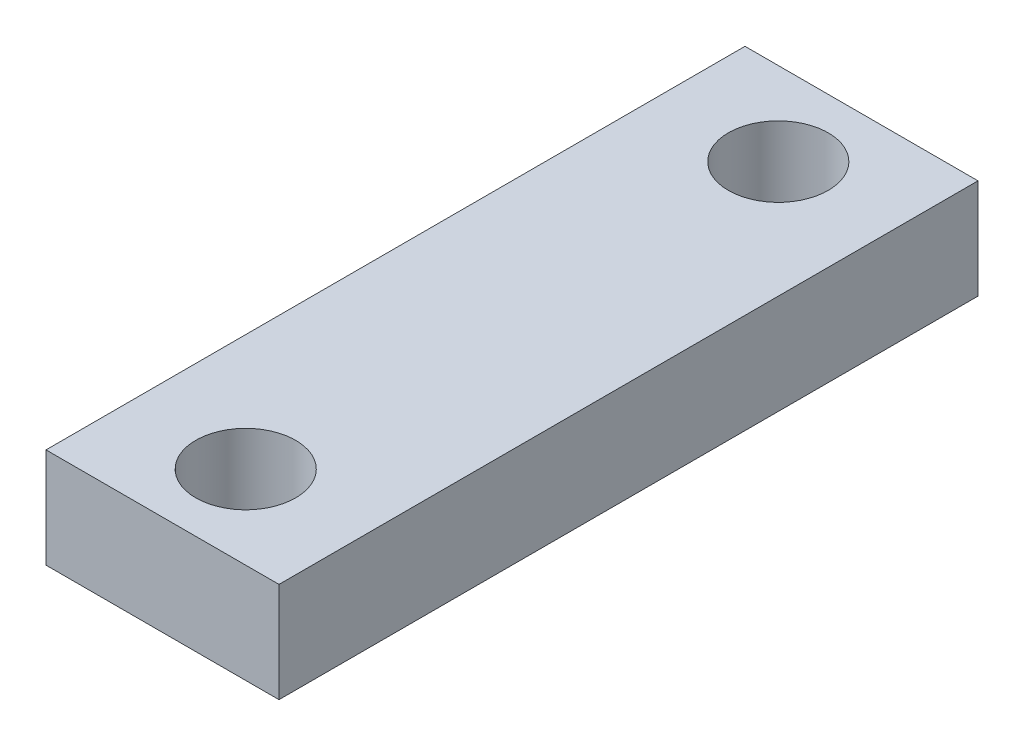
SolidWorks part; units mm, degrees
material "Alloy Steel"
ref_plane "Front Plane" through (0, 0, 0) normal (0, 0, 1) x (1, 0, 0)
ref_plane "Top Plane" through (0, 0, 0) normal (0, 1, 0) x (1, 0, 0)
ref_plane "Right Plane" through (0, 0, 0) normal (1, 0, 0) x (0, 0, -1)
sketch "Sketch1" plane through (0, 0, 0) normal (0, 1, 0) x (1, 0, 0)
  line L0 (7, -21) -> (7, 21)
  line L1 (7, 21) -> (-7, 21)
  line L2 (-7, 21) -> (-7, -21)
  line L3 (-7, -21) -> (7, -21)
  circle A0 centre (0, 16) radius 3
  circle A1 centre (0, -16) radius 3
extrude "Boss-Extrude1" add sketch "Sketch1" along normal blind 6
